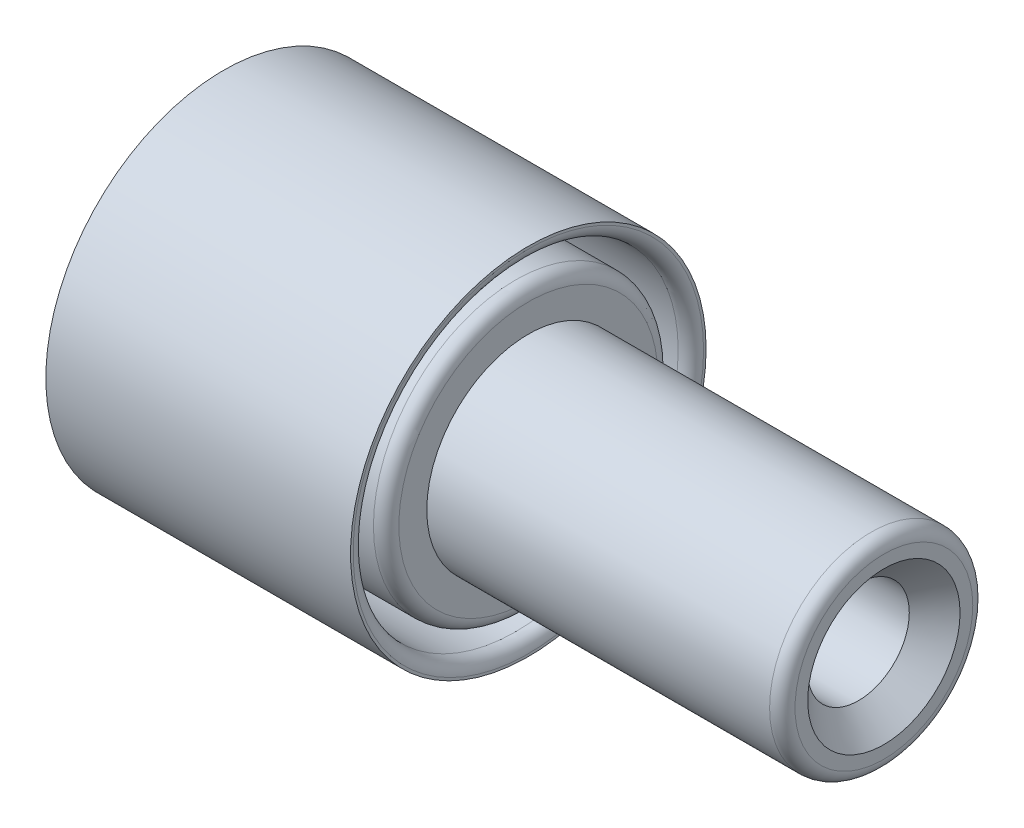
SolidWorks part; units mm, degrees
ref_plane "前视基准面" through (0, 0, 0) normal (0, 0, 1) x (1, 0, 0)
ref_plane "上视基准面" through (0, 0, 0) normal (0, 1, 0) x (1, 0, 0)
ref_plane "右视基准面" through (0, 0, 0) normal (1, 0, 0) x (0, 0, -1)
sketch "草图1" plane through (0, 0, 0) normal (1, 0, 0) x (0, 0, -1)
  circle A0 centre (0, 0) radius 7
  dimension "D1" = 14
extrude "凸台-拉伸1" add sketch "草图1" along normal blind 12
sketch "草图2" plane through (12, 0, 0) normal (1, 0, 0) x (0, 0, -1)
  circle A1 centre (0, 0) radius 6 construction
  circle A2 centre (0, 0) radius 7
  circle A3 centre (0, 0) radius 7
  circle A4 centre (0, 0) radius 6.4
  circle A5 centre (0, 0) radius 5.6
  dimension "D2" = 0.4
  dimension "D3" = 0.4
  dimension "D4" = 12
  dimension "D1" = 0
extrude "切除-拉伸1" cut sketch "草图2" against normal blind 10 contours A4 A5
sketch "草图3" plane through (12, 0, 0) normal (1, 0, 0) x (0, 0, -1)
  circle A0 centre (0, 0) radius 4
  dimension "D1" = 8
extrude "凸台-拉伸2" add sketch "草图3" along normal blind 14
sketch "草图4" plane through (26, 0, 0) normal (1, 0, 0) x (0, 0, -1)
  circle A0 centre (0, 0) radius 2
  dimension "D1" = 4
extrude "切除-拉伸2" cut sketch "草图4" against normal through all
chamfer "倒角1" distance 1.5 angle 45 1 edges at (0, 0, -2)
chamfer "倒角2" distance 1 angle 45 1 edges at (26, 0, -2)
fillet "圆角1" radius 0.5 3 edges at (12, 0, -6.4) (12, 0, -5.6) (26, 0, -4)
